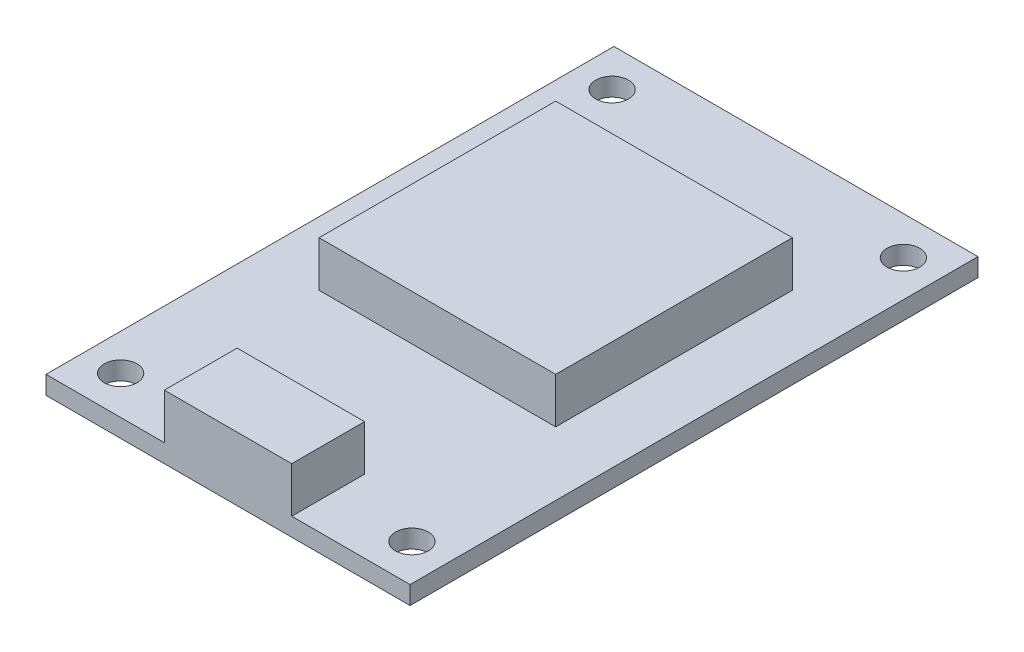
SolidWorks part; units mm, degrees
ref_plane "Front Plane" through (0, 0, 0) normal (0, 0, 1) x (1, 0, 0)
ref_plane "Top Plane" through (0, 0, 0) normal (0, 1, 0) x (1, 0, 0)
ref_plane "Right Plane" through (0, 0, 0) normal (1, 0, 0) x (0, 0, -1)
sketch "Sketch1" plane through (0, 0, 0) normal (0, 1, 0) x (1, 0, 0)
  line L1 (-12.7, -19.812) -> (12.7, -19.812)
  line L2 (-12.7, -19.812) -> (-12.7, 19.812)
  line L3 (-12.7, 19.812) -> (12.7, 19.812)
  line L4 (12.7, -19.812) -> (12.7, 19.812)
  line L5 (-12.7, -19.812) -> (12.7, 19.812) construction
  line L6 (-12.7, 19.812) -> (12.7, -19.812) construction
  line L7 (-10.16, -17.145) -> (10.16, -17.145) construction
  line L8 (-10.16, -17.145) -> (-10.16, 17.145) construction
  line L9 (-10.16, 17.145) -> (10.16, 17.145) construction
  line L10 (10.16, -17.145) -> (10.16, 17.145) construction
  line L11 (-10.16, -17.145) -> (10.16, 17.145) construction
  line L12 (-10.16, 17.145) -> (10.16, -17.145) construction
  circle A0 centre (10.16, 17.145) radius 1.143
  circle A1 centre (-10.16, 17.145) radius 1.143
  circle A2 centre (-10.16, -17.145) radius 1.143
  circle A3 centre (10.16, -17.145) radius 1.143
  point P0 (0, 0)
  point P6 (0, 0)
  dimension "D5" = 2.286
  dimension "D1" = 25.4
  dimension "D2" = 39.624
  dimension "D3" = 20.32
  dimension "D4" = 34.29
extrude "Boss-Extrude1" add sketch "Sketch1" along normal blind 1.27
sketch "Sketch2" plane through (0, 1.27, 0) normal (0, 1, 0) x (1, 0, 0)
  line L0 (0, 0) -> (0, 50000) construction
  line L1 (-12.7, -19.812) -> (12.7, -19.812) construction
  line L2 (-8.255, -5.207) -> (8.255, -5.207)
  line L3 (-8.255, -5.207) -> (-8.255, 11.303)
  line L4 (-8.255, 11.303) -> (8.255, 11.303)
  line L5 (8.255, -5.207) -> (8.255, 11.303)
  line L6 (-8.255, -5.207) -> (8.255, 11.303) construction
  line L7 (-8.255, 11.303) -> (8.255, -5.207) construction
  point P3 (0, 3.048)
  dimension "D1" = 16.51
  dimension "D2" = 16.51
  dimension "D3" = 22.86
extrude "Boss-Extrude2" add sketch "Sketch2" along normal blind 3.175
sketch "Sketch3" plane through (0, 1.27, 0) normal (0, 1, 0) x (1, 0, 0)
  line L0 (0, 0) -> (0, 50000) construction
  line L1 (-12.7, -19.812) -> (12.7, -19.812) construction
  line L2 (-4.445, -14.732) -> (4.445, -14.732)
  line L3 (-4.445, -14.732) -> (-4.445, -19.812)
  line L4 (-4.445, -19.812) -> (4.445, -19.812)
  line L5 (4.445, -14.732) -> (4.445, -19.812)
  line L6 (-4.445, -14.732) -> (4.445, -19.812) construction
  line L7 (-4.445, -19.812) -> (4.445, -14.732) construction
  point P3 (0, -17.272)
  dimension "D1" = 8.89
  dimension "D2" = 5.08
extrude "Boss-Extrude3" add sketch "Sketch3" along normal blind 3.175
